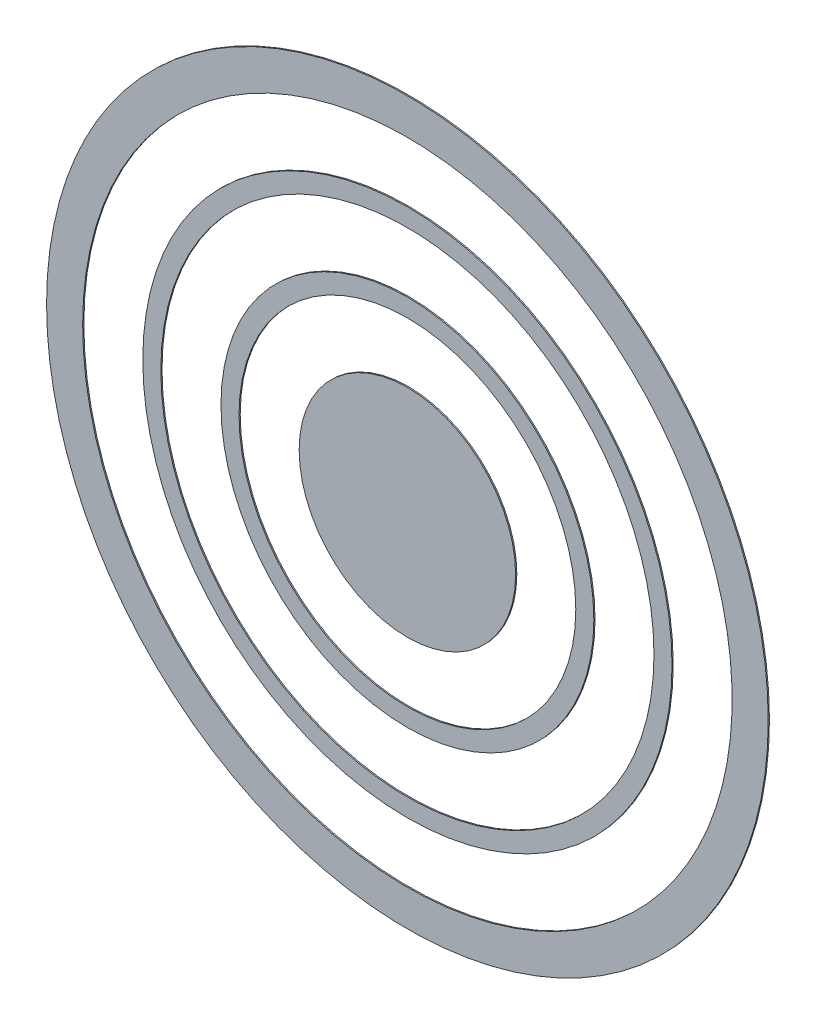
SolidWorks part; units mm, degrees
material "ABS"
ref_plane "Front" through (0, 0, 0) normal (0, 0, 1) x (1, 0, 0)
ref_plane "Top" through (0, 0, 0) normal (0, 1, 0) x (1, 0, 0)
ref_plane "Right" through (0, 0, 0) normal (1, 0, 0) x (0, 0, -1)
sketch "Эскиз1" plane through (0, 0, 0) normal (0, 0, 1) x (1, 0, 0)
  line L0 (0, 0.9) -> (0, 1.4) construction
  line L1 (0, 1.55) -> (0, 2.05) construction
  line L2 (0, 2.2) -> (0, 2.7) construction
  circle A0 centre (0, 0) radius 3
  circle A1 centre (0, 0) radius 2.7
  circle A2 centre (0, 0) radius 2.2
  circle A3 centre (0, 0) radius 2.05
  circle A4 centre (0, 0) radius 0.9
  circle A5 centre (0, 0) radius 1.4
  circle A6 centre (0, 0) radius 1.55
  dimension "D1" = 6
  dimension "D2" = 0.3
  dimension "D3" = 0.15
  dimension "D4" = 1.8
  dimension "D6" = 0.15
extrude "Бобышка-Вытянуть1" add sketch "Эскиз1" along normal blind 0.01 contours A0 A1 | A2 A3 | A6 A5 | A4
